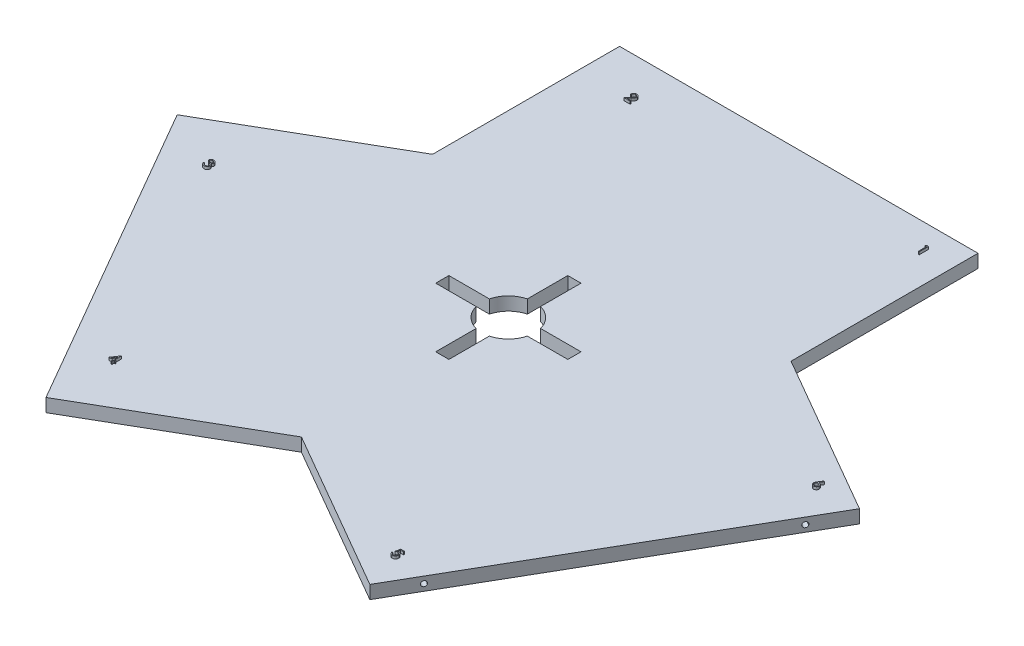
SolidWorks part; units mm, degrees
ref_plane "Front Plane" through (0, 0, 0) normal (0, 0, 1) x (1, 0, 0)
ref_plane "Top Plane" through (0, 0, 0) normal (0, 1, 0) x (1, 0, 0)
ref_plane "Right Plane" through (0, 0, 0) normal (1, 0, 0) x (0, 0, -1)
sketch "Sketch1" plane through (0, 0, 0) normal (0, 1, 0) x (1, 0, 0)
  line L0 (125, 0) -> (0, 0) construction
  line L1 (0, 0) -> (0, 125) construction
  line L2 (0, 0) -> (-52.8273, 113.2885) construction
  line L3 (-52.8273, 113.2885) -> (-52.8273, 109.9285) construction
  line L4 (-52.8273, 113.2885) -> (-7.8273, 113.2885) construction
  line L5 (-38.3273, 109.9285) -> (-67.3273, 109.9285) construction
  line L6 (-67.3273, 109.9285) -> (-67.3273, 63.9285) construction
  line L7 (-67.3273, 63.9285) -> (-38.3273, 63.9285) construction
  line L8 (-38.3273, 63.9285) -> (-38.3273, 109.9285) construction
  line L9 (67.3273, 63.9285) -> (38.3273, 63.9285) construction
  line L10 (67.3273, 109.9285) -> (67.3273, 63.9285) construction
  line L11 (38.3273, 109.9285) -> (67.3273, 109.9285) construction
  line L12 (38.3273, 63.9285) -> (38.3273, 109.9285) construction
  line L13 (0, 0) -> (52.8273, 113.2885) construction
  line L14 (52.8273, 113.2885) -> (52.8273, 109.9285) construction
  line L15 (52.8273, 113.2885) -> (7.8273, 113.2885) construction
  line L16 (124.5243, -10.8945) -> (121.6145, -9.2145) construction
  line L17 (124.5243, -10.8945) -> (102.0243, -49.8656) construction
  line L18 (114.3645, -21.7718) -> (128.8645, 3.3429) construction
  line L20 (128.8645, 3.3429) -> (89.0273, 26.3429) construction
  line L21 (89.0273, 26.3429) -> (74.5273, 1.2282) construction
  line L22 (74.5273, 1.2282) -> (114.3645, -21.7718) construction
  line L23 (21.7, -90.2714) -> (36.2, -65.1566) construction
  line L24 (61.5372, -113.2714) -> (21.7, -90.2714) construction
  line L25 (76.0372, -88.1566) -> (61.5372, -113.2714) construction
  line L26 (36.2, -65.1566) -> (76.0372, -88.1566) construction
  line L27 (71.6971, -102.394) -> (68.7872, -100.714) construction
  line L28 (71.6971, -102.394) -> (94.1971, -63.4229) construction
  line L29 (0, 0) -> (71.6971, -102.394) construction
  line L30 (0, 0) -> (124.5243, -10.8945) construction
  line L31 (-71.6971, -102.394) -> (-68.7872, -100.714) construction
  line L32 (-71.6971, -102.394) -> (-94.1971, -63.4229) construction
  line L33 (-76.0372, -88.1566) -> (-61.5372, -113.2714) construction
  line L34 (-61.5372, -113.2714) -> (-21.7, -90.2714) construction
  line L35 (-21.7, -90.2714) -> (-36.2, -65.1566) construction
  line L37 (-36.2, -65.1566) -> (-76.0372, -88.1566) construction
  line L38 (-89.0273, 26.3429) -> (-74.5273, 1.2282) construction
  line L39 (-128.8645, 3.3429) -> (-89.0273, 26.3429) construction
  line L40 (-114.3645, -21.7718) -> (-128.8645, 3.3429) construction
  line L41 (-74.5273, 1.2282) -> (-114.3645, -21.7718) construction
  line L42 (-124.5243, -10.8945) -> (-121.6145, -9.2145) construction
  line L43 (-124.5243, -10.8945) -> (-102.0243, -49.8656) construction
  line L44 (0, 0) -> (-124.5243, -10.8945) construction
  line L45 (0, 0) -> (-71.6971, -102.394) construction
  line L46 (-67.8273, 109.9285) -> (67.8273, 109.9285)
  line L47 (67.8273, 109.9285) -> (67.8273, 39.1601)
  line L48 (67.8273, 39.1601) -> (129.1145, 3.7759)
  line L49 (129.1145, 3.7759) -> (61.2872, -113.7044)
  line L50 (61.2872, -113.7044) -> (0, -78.3202)
  line L68 (0, -78.3202) -> (-61.2872, -113.7044)
  line L69 (-61.2872, -113.7044) -> (-129.1145, 3.7759)
  line L70 (-129.1145, 3.7759) -> (-67.8273, 39.1601)
  line L71 (-67.8273, 39.1601) -> (-67.8273, 109.9285)
  line L72 (-2.5, 9.6825) -> (-2.5, 25)
  line L73 (25, -2.5) -> (9.6825, -2.5)
  line L74 (25, -2.5) -> (25, 2.5)
  line L75 (25, 2.5) -> (9.6825, 2.5)
  line L76 (-25, -2.5) -> (-25, 2.5)
  line L77 (25, -2.5) -> (-25, 2.5) construction
  line L78 (25, 2.5) -> (-25, -2.5) construction
  line L79 (-2.5, -25) -> (2.5, -25)
  line L80 (-2.5, -25) -> (-2.5, -9.6825)
  line L81 (-2.5, 25) -> (2.5, 25)
  line L82 (2.5, -25) -> (2.5, -9.6825)
  line L83 (-2.5, -25) -> (2.5, 25) construction
  line L84 (-2.5, 25) -> (2.5, -25) construction
  line L85 (-9.6825, 2.5) -> (-25, 2.5)
  line L86 (-9.6825, -2.5) -> (-25, -2.5)
  line L87 (2.5, -0.25) -> (2.5, 0.25)
  line L88 (2.5, 9.6825) -> (2.5, 25)
  circle A2 centre (0, 0) radius 125 construction
  arc A3 (-2.5, 9.6825) -> (-9.6825, 2.5) centre (0, 0) ccw
  arc A4 (2.5, -9.6825) -> (9.6825, -2.5) centre (0, 0) ccw
  arc A5 (-9.6825, -2.5) -> (-2.5, -9.6825) centre (0, 0) ccw
  arc A6 (9.6825, 2.5) -> (2.5, 9.6825) centre (0, 0) ccw
  point P0 (-70.2421, -101.554)
  point P6 (-7.8945, 119.3282)
  point P12 (-99.394, -66.5009)
  point P14 (-52.8273, 109.9285)
  point P31 (121.6145, -9.2145)
  point P46 (-68.7872, -100.714)
  point P55 (0, 0)
  dimension "D1" = 250
  dimension "D18" = 50
  dimension "D17" = 20
  dimension "D2" = 3.36
  dimension "D3" = 45
  dimension "D4" = 29
  dimension "D5" = 46
  dimension "D6" = 50
  dimension "D7" = 3
  dimension "D9" = 15
  dimension "D10" = 15
  dimension "D11" = 15
  dimension "D12" = 15
  dimension "D13" = 15
  dimension "D8" = 15
  dimension "D19" = 50
  dimension "D20" = 5
  dimension "D21" = 5
extrude "Boss-Extrude1" add sketch "Sketch1" along normal blind 5 contours L71 L70 L69 L68 L50 L49 L48 L47 L46 A6 L75 L74 L73 A4 L82 L79 L80 A5 L86 L76 L85 A3 L72 L81 L88
sketch "Sketch2" plane through (0, 5, 0) normal (0, 1, 0) x (1, 0, 0)
  text T0 "1"
  text T1 "2"
  text T2 "3"
  text T3 "4"
  text T4 "5"
  text T5 "6"
  point P1 (55.6787, 98.294)
  point P4 (-49.3622, 92.9504)
  point P5 (-107.6417, -8.7586)
  point P6 (-61.7182, -90.448)
  point P7 (55.6787, -100.7916)
  point P8 (112.6141, 1.5667)
extrude "Boss-Extrude2" add sketch "Sketch2" along normal blind 1
sketch "Sketch3" plane through (0, 0, -109.9285) normal (0, 0, -1) x (-1, 0, 0)
  line L0 (-67.8273, 2.5) -> (-52.8273, 2.5) construction
  line L1 (-67.8273, 5) -> (-67.8273, 0) construction
  line L2 (0, 0) -> (0, 5) construction
  line L3 (67.8273, 0) -> (-67.8273, 0) construction
  line L4 (67.8273, 5) -> (-67.8273, 5) construction
  circle A0 centre (-52.8273, 2.5) radius 1
  circle A1 centre (52.8273, 2.5) radius 1
  dimension "D2" = 2
  dimension "D1" = 15
extrude "Cut-Extrude1" cut sketch "Sketch3" against normal blind 10
pattern_circular "CirPattern1" count 3 over 360 about axis through (0, 0, 0) along (0, 1, 0) of "Cut-Extrude1"
